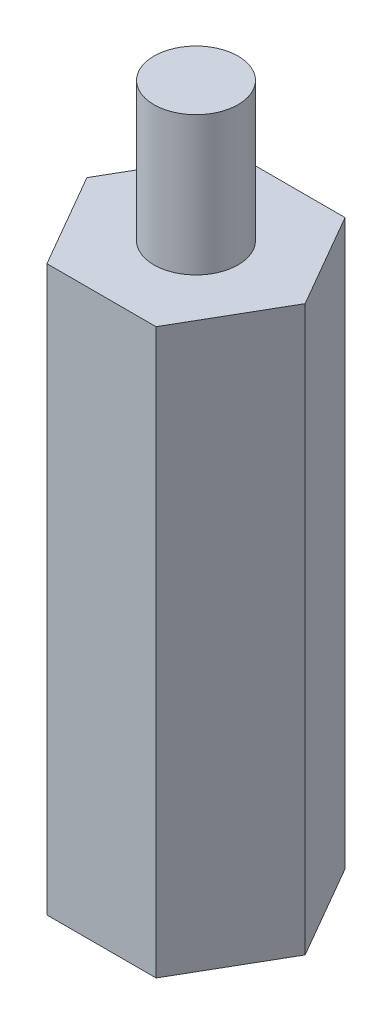
SolidWorks part; units mm, degrees
material "Chrome Stainless Steel"
ref_plane "Front Plane" through (0, 0, 0) normal (0, 0, 1) x (1, 0, 0)
ref_plane "Top Plane" through (0, 0, 0) normal (0, 1, 0) x (1, 0, 0)
ref_plane "Right Plane" through (0, 0, 0) normal (1, 0, 0) x (0, 0, -1)
sketch "Sketch1" plane through (0, 0, 0) normal (0, 1, 0) x (1, 0, 0)
  line L0 (0, 0) -> (3.695, 0) construction
  line L1 (1.8475, 3.2) -> (-1.8475, 3.2)
  line L2 (-1.8475, 3.2) -> (-3.695, 0)
  line L3 (-3.695, 0) -> (-1.8475, -3.2)
  line L4 (-1.8475, -3.2) -> (1.8475, -3.2)
  line L5 (1.8475, -3.2) -> (3.695, 0)
  line L6 (3.695, 0) -> (1.8475, 3.2)
  circle A0 centre (0, 0) radius 3.2 construction
  dimension "D1" = 6.4
extrude "Boss-Extrude1" add sketch "Sketch1" along normal blind 19.1
sketch "Sketch2" plane through (0, 19.1, 0) normal (0, 1, 0) x (1, 0, 0)
  circle A0 centre (0, 0) radius 1.425
  dimension "D1" = 2.85
extrude "Boss-Extrude2" add sketch "Sketch2" along normal blind 4.7
sketch "Sketch3" plane through (0, 0, 0) normal (0, -1, 0) x (1, 0, 0)
  circle A0 centre (0, 0) radius 1.425
  dimension "D1" = 2.85
extrude "Cut-Extrude1" cut sketch "Sketch3" against normal blind 4
